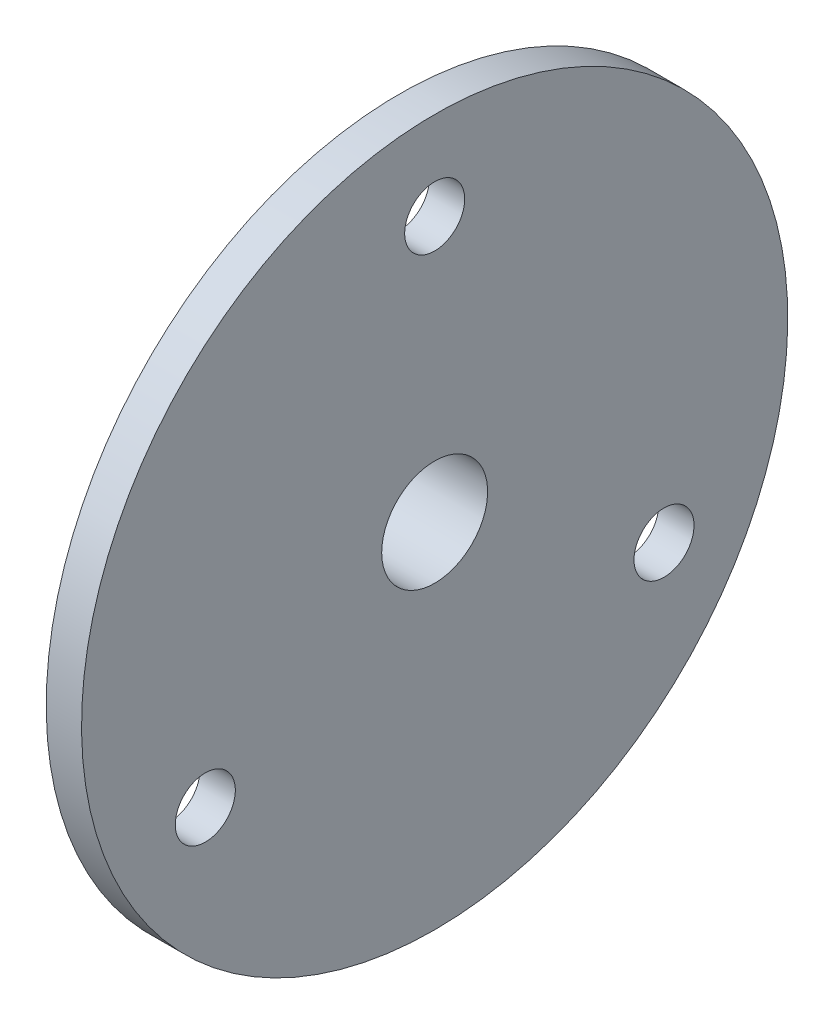
SolidWorks part; units mm, degrees
ref_plane "Plan de face" through (0, 0, 0) normal (0, 0, 1) x (1, 0, 0)
ref_plane "Plan de dessus" through (0, 0, 0) normal (0, 1, 0) x (1, 0, 0)
ref_plane "Plan de droite" through (0, 0, 0) normal (1, 0, 0) x (0, 0, -1)
sketch "Esquisse1" plane through (0, 0, 0) normal (0, 0, 1) x (1, 0, 0)
  line L0 (-1031.2311, 0) -> (-1, 0) construction
  line L1 (1, 0) -> (67.5688, 0) construction
  line L2 (-1, 0) -> (1, 0)
  line L3 (1, 0) -> (1, 20)
  line L4 (1, 20) -> (-1, 20)
  line L5 (-1, 5) -> (-1, 20)
  line L6 (-1, 0) -> (-8, 0)
  line L8 (-1, 5) -> (-8, 5)
  line L9 (-8, 0) -> (-8, 5)
  point P11 (0, 0)
  dimension "D1" = 2
  dimension "D2" = 5
  dimension "D3" = 20
  dimension "D4" = 7
revolve "Révolution1" add sketch "Esquisse1" angle 360 about L0
hole_wizard "Diamètre du perçage Ø6.0 (6)1" positions "Esquisse3" profile "Esquisse2" hole size "Ø6.0" standard "Ansi Metric" end condition through all
sketch "Esquisse3" plane through (-8, 0, 0) normal (-1, 0, 0) x (0, 0, 1)
  point P0 (0, 0)
sketch "Esquisse2" plane through (-8, 0, 0) normal (0, 1, 0) x (0, 0, 1)
  line L0 (0, 0) -> (0, 9)
  line L1 (0, 9) -> (3, 9)
  line L2 (3, 9) -> (3, 0)
  line L5 (3, 0) -> (0, 0)
  line L11 (0, -6.35) -> (0, 107.95) construction
  dimension "Diamètre du perçage jusqu'au prochain" = 6
  dimension "Profondeur du perçage jusqu'au prochain" = 9
hole_wizard "Trou taraudé M4x0.71" positions "Esquisse3D1" profile "Esquisse4" tap size "M4x0.7" standard "Ansi Metric"
sketch3d "Esquisse3D1"
  point P0 (-4.5, 5, 0)
  dimension "D1" = 3.5
sketch "Esquisse4" plane through (-4.5, 5, 0) normal (1, 0, 0) x (0, 0, 1)
  line L0 (0, 0) -> (0, 4.9914)
  line L1 (0, 4.9914) -> (1.65, 4)
  line L2 (1.65, 4) -> (1.65, 0)
  line L5 (1.65, 0) -> (0, 0)
  line L10 (0, 4.9914) -> (-1.65, 4) construction
  line L11 (0, -6.35) -> (0, 107.95) construction
  dimension "Diamètre du trou pour taraudage" = 3.3
  dimension "Profondeur du trou pour taraudage" = 4
  dimension "Angle de pointe" = 118
cosmetic thread "Filetage de perçage1" parameters "D1"=2.4945, "D2"=4
hole_wizard "Dégagement M31" positions "Esquisse6" profile "Esquisse5" hole size "M3" standard "Ansi Metric" end condition through all
sketch "Esquisse6" plane through (-1, 0, 0) normal (-1, 0, 0) x (0, 0, 1)
  line L0 (-12.9904, -7.5) -> (12.9904, -7.5)
  line L1 (12.9904, -7.5) -> (0, 15)
  line L2 (0, 15) -> (-12.9904, -7.5)
  circle A0 centre (0, 0) radius 15 construction
  point P0 (0, 15)
  point P2 (12.9904, -7.5)
  point P4 (-12.9904, -7.5)
  dimension "D1" = 30
sketch "Esquisse5" plane through (-1, 15, 0) normal (0, 1, 0) x (0, 0, 1)
  line L0 (0, 0) -> (0, 2)
  line L1 (0, 2) -> (1.7, 2)
  line L2 (1.7, 2) -> (1.7, 0)
  line L5 (1.7, 0) -> (0, 0)
  line L11 (0, -6.35) -> (0, 107.95) construction
  dimension "Diamètre du perçage jusqu'au prochain" = 3.4
  dimension "Profondeur du perçage jusqu'au prochain" = 2
